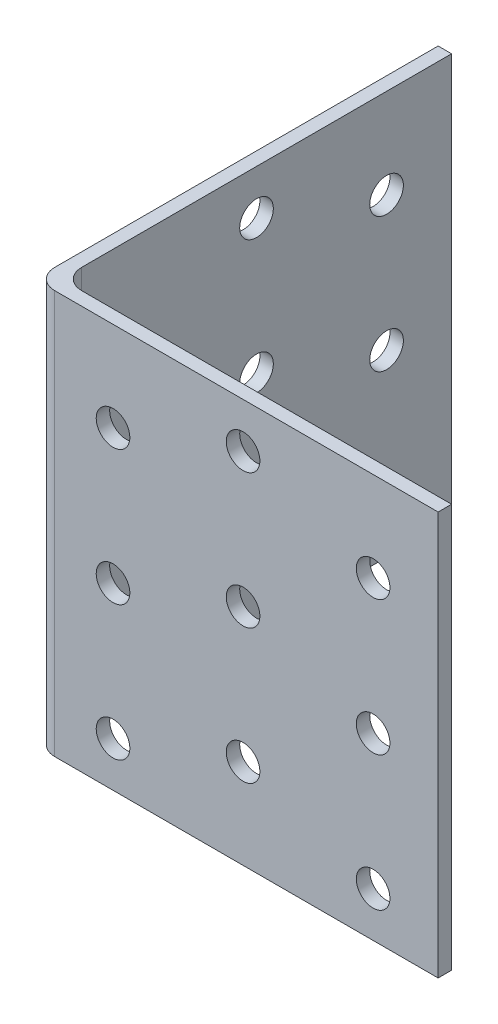
SolidWorks part; units mm, degrees
ref_plane "Front Plane" through (0, 0, 0) normal (0, 0, 1) x (1, 0, 0)
ref_plane "Top Plane" through (0, 0, 0) normal (0, 1, 0) x (1, 0, 0)
ref_plane "Right Plane" through (0, 0, 0) normal (1, 0, 0) x (0, 0, -1)
sketch "Sketch1" plane through (0, 0, 0) normal (0, 1, 0) x (1, 0, 0)
  line L0 (0, 3) -> (0, 60)
  line L1 (0, 60) -> (2, 60)
  line L2 (2, 60) -> (2, 5)
  line L3 (5, 2) -> (60, 2)
  line L4 (60, 2) -> (60, 0)
  line L5 (60, 0) -> (3, 0)
  arc A0 (0, 3) -> (3, 0) centre (3, 3) ccw
  arc A1 (2, 5) -> (5, 2) centre (5, 5) ccw
  dimension "D1" = 3
  dimension "D3" = 2
  dimension "D4" = 2
extrude "Boss-Extrude1" add sketch "Sketch1" along normal mid plane 60
sketch "Sketch2" plane through (0, 0, -2) normal (0, 0, -1) x (-1, 0, 0)
  line L0 (-60, 30) -> (-5, 30) construction
  line L1 (-60, 30) -> (-60, -30) construction
  line L2 (-60, -30) -> (-5, -30) construction
  circle A0 centre (-50.3333, -23.3333) radius 2.5
  circle A1 centre (-50.3333, -3.3333) radius 2.5
  circle A2 centre (-50.3333, 16.6667) radius 2.5
  circle A3 centre (-31, 23.3333) radius 2.5
  circle A4 centre (-31, 3.3333) radius 2.5
  circle A5 centre (-31, -16.6667) radius 2.5
  circle A6 centre (-11.6667, -23.3333) radius 2.5
  circle A7 centre (-11.6667, -3.3333) radius 2.5
  circle A8 centre (-11.6667, 16.6667) radius 2.5
  dimension "D1" = 5
  dimension "D2" = 5
  dimension "D3" = 5
  dimension "D8" = 5
  dimension "D9" = 5
  dimension "D10" = 5
  dimension "D15" = 5
  dimension "D16" = 5
  dimension "D17" = 5
  dimension "D18" = 19.3333
  dimension "D4" = 9.6667
  dimension "D5" = 6.6667
  dimension "D6" = 20
  dimension "D7" = 20
  dimension "D11" = 29
  dimension "D12" = 20
  dimension "D13" = 20
  dimension "D14" = 6.6667
  dimension "D19" = 20
  dimension "D20" = 20
  dimension "D21" = 6.6667
extrude "Cut-Extrude1" cut sketch "Sketch2" against normal blind 10
sketch "Sketch3" plane through (0, 0, 0) normal (1, 0, 0) x (0, 0, -1)
  line L0 (0, 30) -> (0, -30) construction
ref_plane "Plane1" through (0, 0, 0) normal (0.7071, 0, 0.7071) x (0, -1, 0)
mirror "Mirror9" about plane through (0, 0, 0) normal (0.7071, 0, 0.7071) of "Cut-Extrude1"
